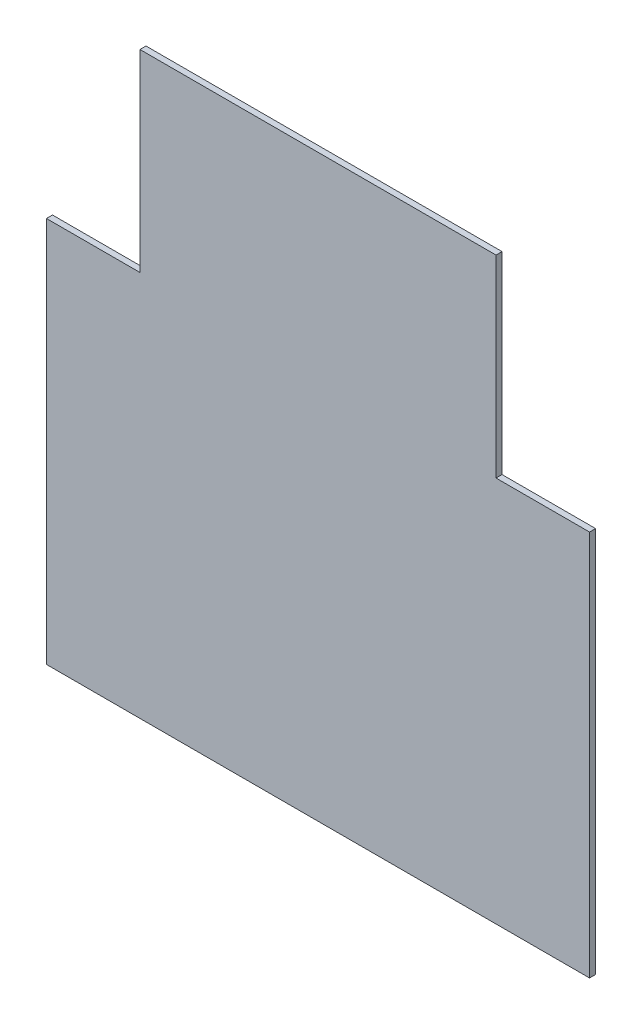
SolidWorks part; units mm, degrees
ref_plane "Front Plane" through (0, 0, 0) normal (0, 0, 1) x (1, 0, 0)
ref_plane "Top Plane" through (0, 0, 0) normal (0, 1, 0) x (1, 0, 0)
ref_plane "Right Plane" through (0, 0, 0) normal (1, 0, 0) x (0, 0, -1)
sketch "Sketch1" plane through (0, 0, 0) normal (0, 0, 1) x (1, 0, 0)
  line L0 (93.6625, 101.6) -> (142.875, 101.6)
  line L1 (-142.875, 101.6) -> (-93.6625, 101.6)
  line L2 (-142.875, 101.6) -> (-142.875, -101.6)
  line L3 (-142.875, -101.6) -> (142.875, -101.6)
  line L4 (142.875, 101.6) -> (142.875, -101.6)
  line L5 (-142.875, 101.6) -> (142.875, -101.6) construction
  line L6 (-142.875, -101.6) -> (142.875, 101.6) construction
  line L7 (-93.6625, 203.2) -> (93.6625, 203.2)
  line L8 (-93.6625, 203.2) -> (-93.6625, 101.6)
  line L10 (93.6625, 203.2) -> (93.6625, 101.6)
  line L11 (-93.6625, 203.2) -> (93.6625, 101.6) construction
  line L12 (-93.6625, 101.6) -> (93.6625, 203.2) construction
  point P0 (0, 0)
  point P6 (0, 152.4)
  point P11 (0, 0)
  dimension "D1" = 285.75
  dimension "D2" = 101.6
  dimension "D3" = 203.2
  dimension "D4" = 187.325
extrude "Boss-Extrude1" add sketch "Sketch1" along normal blind 3.175
